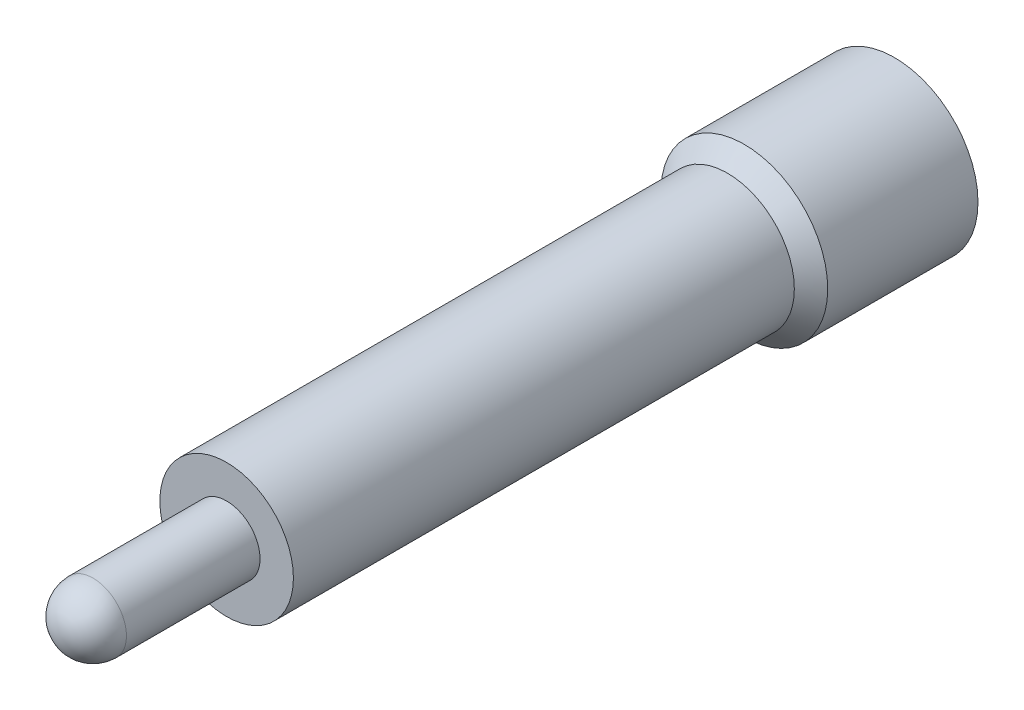
SolidWorks part; units mm, degrees
ref_plane "Спереди" through (0, 0, 0) normal (0, 0, 1) x (1, 0, 0)
ref_plane "Сверху" through (0, 0, 0) normal (0, 1, 0) x (1, 0, 0)
ref_plane "Справа" through (0, 0, 0) normal (1, 0, 0) x (0, 0, -1)
sketch "Эскиз1" plane through (0, 0, 0) normal (0, 0, 1) x (1, 0, 0)
  circle A0 centre (0, 0) radius 5
extrude "Бобышка-Вытянуть1" add sketch "Эскиз1" along normal blind 10
chamfer "Фаска1" distance 1 angle 45 1 edges at (5, 0, 10)
sketch "Эскиз2" plane through (0, 0, 10) normal (0, 0, 1) x (1, 0, 0)
  circle A0 centre (0, 0) radius 4
extrude "Бобышка-Вытянуть2" add sketch "Эскиз2" along normal blind 30
sketch "Эскиз3" plane through (0, 0, 40) normal (0, 0, 1) x (1, 0, 0)
  circle A0 centre (0, 0) radius 2
extrude "Бобышка-Вытянуть3" add sketch "Эскиз3" along normal blind 10
fillet "Скругление1" radius 2 1 edges at (2, 0, 50)
